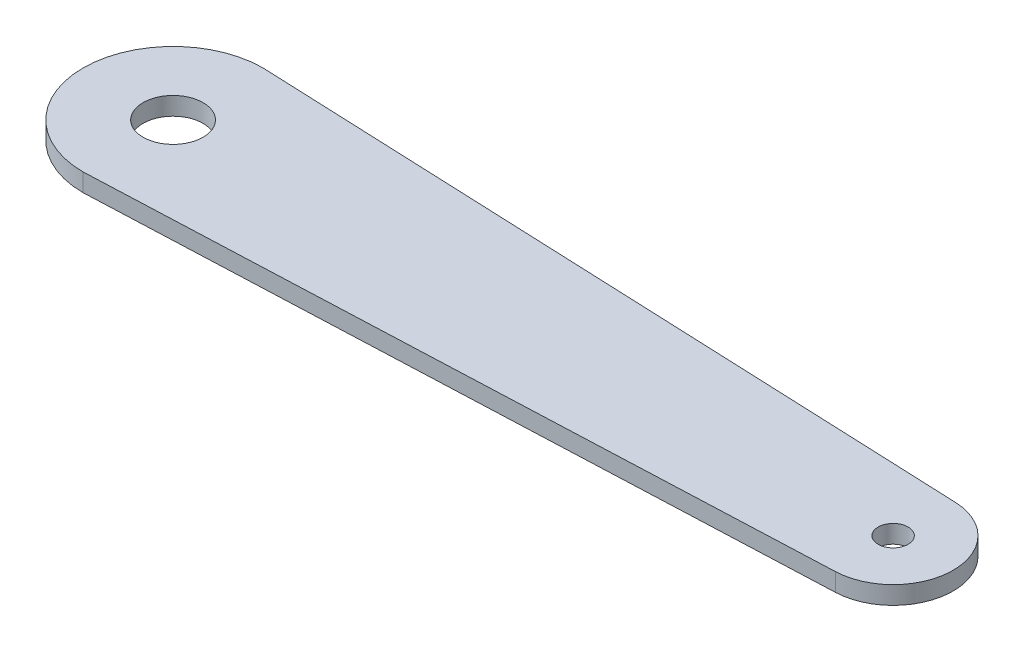
SolidWorks part; units mm, degrees
ref_plane "前视基准面" through (0, 0, 0) normal (0, 0, 1) x (1, 0, 0)
ref_plane "上视基准面" through (0, 0, 0) normal (0, 1, 0) x (1, 0, 0)
ref_plane "右视基准面" through (0, 0, 0) normal (1, 0, 0) x (0, 0, -1)
other "Configuration Table"
sketch "草图1" plane through (0, 0, 0) normal (0, 1, 0) x (1, 0, 0)
  line L0 (0, 0) -> (120, 0)
  line L1 (0, 15) -> (120.4156, 9.9914)
  line L2 (0, -15) -> (120.4156, -9.9914)
  circle A0 centre (0, 0) radius 15
  circle A1 centre (120, 0) radius 10
  circle A2 centre (0, 0) radius 5
  dimension "D1" = 30
  dimension "D3" = 20
  dimension "D4" = 10
  dimension "D2" = 120
extrude "凸台-拉伸1" add sketch "草图1" along normal blind 3
sketch "草图2" plane through (0, 3, 0) normal (0, 1, 0) x (1, 0, 0)
  circle A0 centre (120, 0) radius 2.5
  dimension "D1" = 5
extrude "切除-拉伸1" cut sketch "草图2" against normal through all
